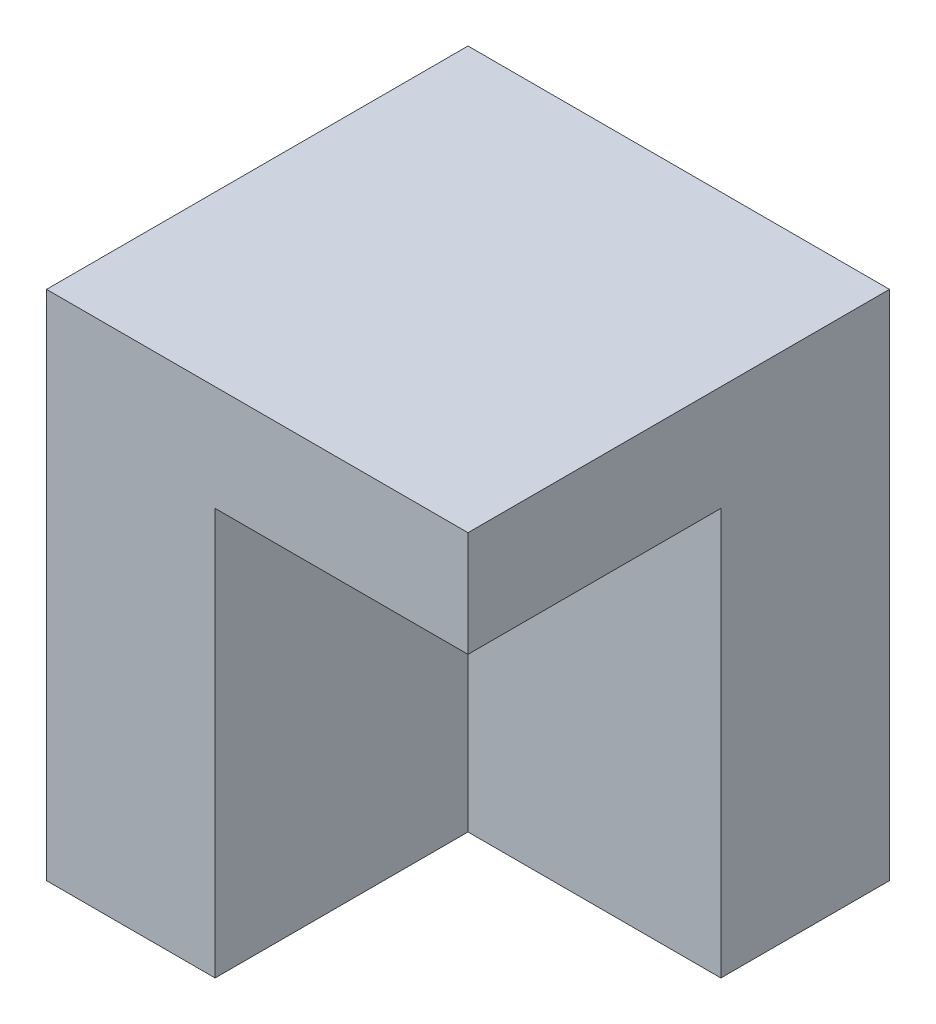
SolidWorks part; units mm, degrees
ref_plane "Front Plane" through (0, 0, 0) normal (0, 0, 1) x (1, 0, 0)
ref_plane "Top Plane" through (0, 0, 0) normal (0, 1, 0) x (1, 0, 0)
ref_plane "Right Plane" through (0, 0, 0) normal (1, 0, 0) x (0, 0, -1)
sketch "Sketch1" plane through (0, 0, 0) normal (0, 1, 0) x (1, 0, 0)
  line L0 (0, 0) -> (10, 0)
  line L5 (2.3029, -10) -> (2.3029, 0) construction
  line L6 (10, -2.3029) -> (0, -2.3029) construction
  line L7 (4, -10) -> (0, -10)
  line L8 (4, -10) -> (4, -4)
  line L10 (0, -10) -> (0, 0)
  line L11 (0, 0) -> (4, -4) construction
  line L14 (10, 0) -> (10, -4)
  line L15 (10, -4) -> (4, -4)
  circle A0 centre (2.3029, -2.3029) radius 1.4
  point P0 (0, 0)
  point P6 (-43, 25.5)
  point P7 (-39.8161, -2.3029)
  point P16 (0, 0)
  point P17 (2.3613, -2.3613)
  point P18 (2.2902, -2.2902)
  point P19 (2.3601, -2.3601)
  dimension "D2" = 2.8
  dimension "D1" = 10
  dimension "D3" = 4
  dimension "D4" = 2.4
extrude "Boss-Extrude1" add sketch "Sketch1" along normal blind 9.65
sketch "Sketch2" plane through (0, 9.65, 0) normal (0, 1, 0) x (1, 0, 0)
  line L1 (0, 0) -> (10, 0)
  line L2 (0, 0) -> (0, -10)
  line L3 (0, -10) -> (10, -10)
  line L4 (10, 0) -> (10, -10)
  dimension "D1" = 10
extrude "Boss-Extrude2" add sketch "Sketch2" along normal blind 2.5
